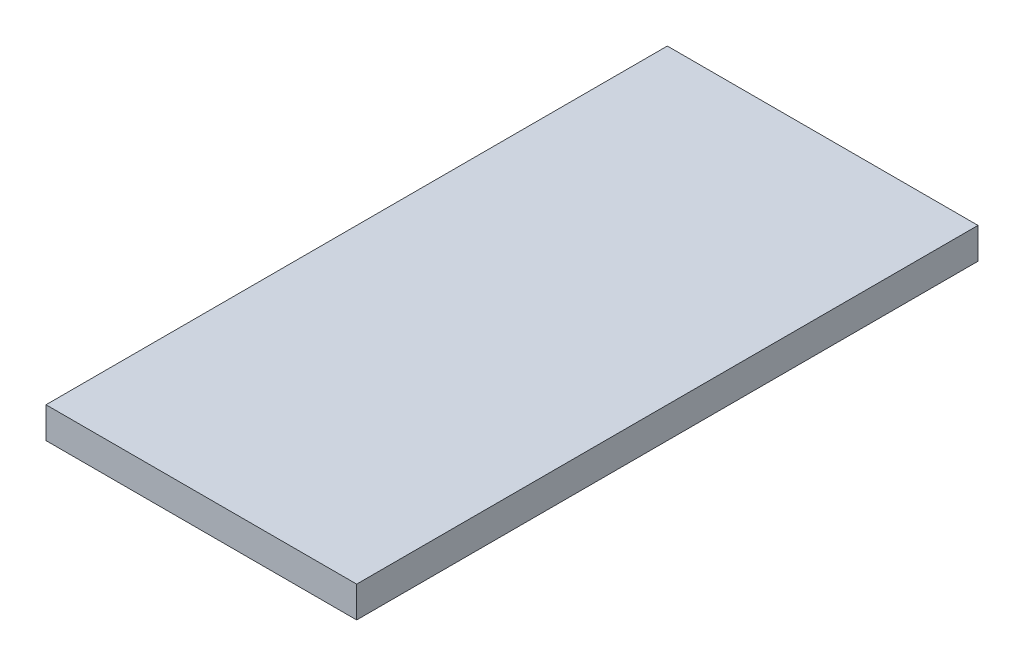
SolidWorks part; units mm, degrees
ref_plane "Front Plane" through (0, 0, 0) normal (0, 0, 1) x (1, 0, 0)
ref_plane "Top Plane" through (0, 0, 0) normal (0, 1, 0) x (1, 0, 0)
ref_plane "Right Plane" through (0, 0, 0) normal (1, 0, 0) x (0, 0, -1)
sketch "Sketch1" plane through (0, 0, 0) normal (0, 1, 0) x (1, 0, 0)
  line L1 (-50, -100) -> (50, -100)
  line L2 (-50, -100) -> (-50, 100)
  line L3 (-50, 100) -> (50, 100)
  line L4 (50, -100) -> (50, 100)
  line L5 (-50, -100) -> (50, 100) construction
  line L6 (-50, 100) -> (50, -100) construction
  point P0 (0, 0)
  dimension "D1" = 100
  dimension "D2" = 200
extrude "Boss-Extrude1" add sketch "Sketch1" along normal blind 10
sketch "Sketch2" plane through (0, 10, 0) normal (0, 1, 0) x (1, 0, 0)
  line L1 (-45, 85) -> (-35, 85)
  line L2 (-45, 85) -> (-45, 95)
  line L3 (-45, 95) -> (-35, 95)
  line L4 (-35, 85) -> (-35, 95)
  line L5 (-45, 85) -> (-35, 95) construction
  line L6 (-45, 95) -> (-35, 85) construction
  point P0 (-40, 90)
  point P5 (-42.9529, 92.7327)
  dimension "D1" = 10
  dimension "D2" = 10
  dimension "D3" = 90
  dimension "D4" = 40
